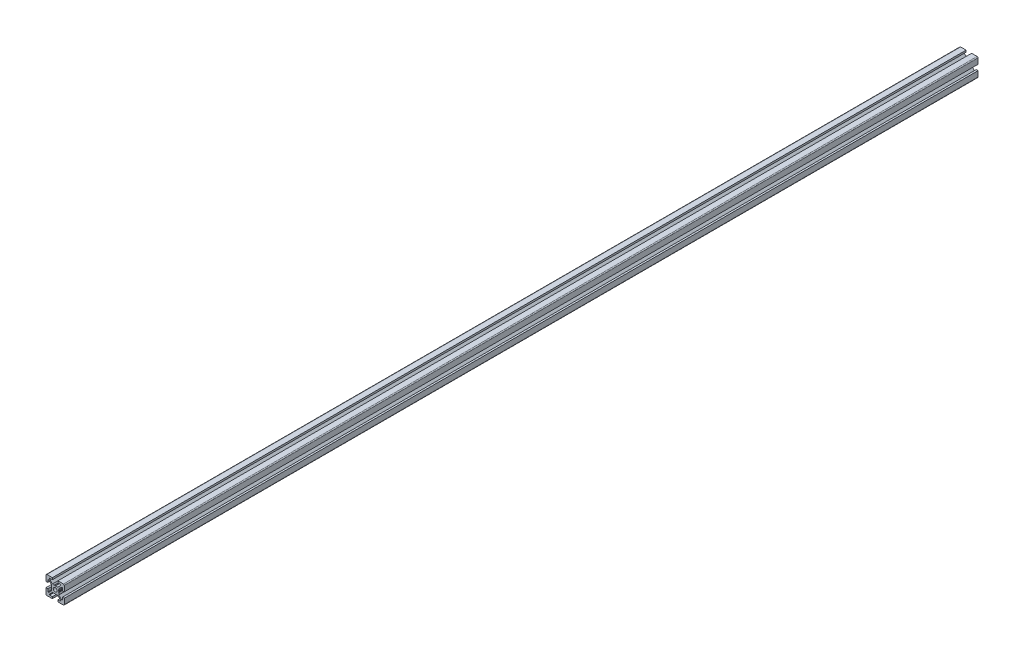
SolidWorks part; units mm, degrees
ref_plane "Front Plane" through (0, 0, 0) normal (0, 0, 1) x (1, 0, 0)
ref_plane "Top Plane" through (0, 0, 0) normal (0, 1, 0) x (1, 0, 0)
ref_plane "Right Plane" through (0, 0, 0) normal (1, 0, 0) x (0, 0, -1)
ref_plane "Plane1" through (0, 0, -2000) normal (0, 0, -1) x (-1, 0, 0)
sketch "Sketch1" plane through (0, 0, -2000) normal (0, 0, -1) x (-1, 0, 0)
  line L0 (10, -3) -> (8, -3)
  line L1 (8, -3) -> (8, -6)
  line L2 (8, -6) -> (7.0607, -6)
  line L3 (7.0607, -6) -> (4, -2.9393)
  line L4 (4, -2.9393) -> (4, -2.5)
  line L5 (4, -2.5) -> (3.751, -1.2189)
  line L6 (3.751, -1.2189) -> (3.933, -0.9036)
  line L7 (3.933, -0.4036) -> (3.7, 0)
  line L8 (3.7, 0) -> (3.933, 0.4036)
  line L9 (4, 0.6536) -> (4, 2.9393)
  line L10 (4, 2.9393) -> (7.0607, 6)
  line L11 (7.0607, 6) -> (8, 6)
  line L12 (8, 6) -> (8, 3)
  line L13 (8, 3) -> (10, 3)
  line L14 (10, 3) -> (10, 9)
  line L15 (9, 10) -> (3, 10)
  line L16 (3, 10) -> (3, 8)
  line L17 (3, 8) -> (6, 8)
  line L18 (6, 8) -> (6, 7.0607)
  line L19 (6, 7.0607) -> (2.9393, 4)
  line L20 (2.9393, 4) -> (2.5, 4)
  line L21 (2.5, 4) -> (1.2189, 3.751)
  line L22 (1.2189, 3.751) -> (0.9036, 3.933)
  line L23 (0.4036, 3.933) -> (0, 3.7)
  line L24 (0, 3.7) -> (-0.4036, 3.933)
  line L25 (-0.6536, 4) -> (-2.9393, 4)
  line L26 (-2.9393, 4) -> (-6, 7.0607)
  line L27 (-6, 7.0607) -> (-6, 8)
  line L28 (-6, 8) -> (-3, 8)
  line L29 (-3, 8) -> (-3, 10)
  line L30 (-3, 10) -> (-9, 10)
  line L31 (-10, 9) -> (-10, 3)
  line L32 (-10, 3) -> (-8, 3)
  line L33 (-8, 3) -> (-8, 6)
  line L34 (-8, 6) -> (-7.0607, 6)
  line L35 (-7.0607, 6) -> (-4, 2.9393)
  line L36 (-4, 2.9393) -> (-4, 2.5)
  line L37 (-4, 2.5) -> (-3.751, 1.2189)
  line L38 (-3.751, 1.2189) -> (-3.933, 0.9036)
  line L39 (-3.933, 0.4036) -> (-3.7, 0)
  line L40 (-3.7, 0) -> (-3.933, -0.4036)
  line L41 (-4, -0.6536) -> (-4, -2.9393)
  line L42 (-4, -2.9393) -> (-7.0607, -6)
  line L43 (-7.0607, -6) -> (-8, -6)
  line L44 (-8, -6) -> (-8, -3)
  line L45 (-8, -3) -> (-10, -3)
  line L46 (-10, -3) -> (-10, -9)
  line L47 (-9, -10) -> (-3, -10)
  line L48 (-3, -10) -> (-3, -8)
  line L49 (-3, -8) -> (-6, -8)
  line L50 (-6, -8) -> (-6, -7.0607)
  line L51 (-6, -7.0607) -> (-2.9393, -4)
  line L52 (-2.9393, -4) -> (-2.5, -4)
  line L53 (-2.5, -4) -> (-1.2189, -3.751)
  line L54 (-1.2189, -3.751) -> (-0.9036, -3.933)
  line L55 (-0.4036, -3.933) -> (0, -3.7)
  line L56 (0, -3.7) -> (0.4036, -3.933)
  line L57 (0.6536, -4) -> (2.9393, -4)
  line L58 (2.9393, -4) -> (6, -7.0607)
  line L59 (6, -7.0607) -> (6, -8)
  line L60 (6, -8) -> (3, -8)
  line L61 (3, -8) -> (3, -10)
  line L62 (3, -10) -> (9, -10)
  line L63 (10, -9) -> (10, -3)
  circle A0 centre (0, 0) radius 2.1
  arc A1 (3.933, -0.9036) -> (3.933, -0.4036) centre (3.5, -0.6536) ccw
  arc A2 (3.933, 0.4036) -> (4, 0.6536) centre (3.5, 0.6536) ccw
  arc A3 (10, 9) -> (9, 10) centre (9, 9) ccw
  arc A4 (0.9036, 3.933) -> (0.4036, 3.933) centre (0.6536, 3.5) ccw
  arc A5 (-0.4036, 3.933) -> (-0.6536, 4) centre (-0.6536, 3.5) ccw
  arc A6 (-9, 10) -> (-10, 9) centre (-9, 9) ccw
  arc A7 (-3.933, 0.9036) -> (-3.933, 0.4036) centre (-3.5, 0.6536) ccw
  arc A8 (-3.933, -0.4036) -> (-4, -0.6536) centre (-3.5, -0.6536) ccw
  arc A9 (-10, -9) -> (-9, -10) centre (-9, -9) ccw
  arc A10 (-0.9036, -3.933) -> (-0.4036, -3.933) centre (-0.6536, -3.5) ccw
  arc A11 (0.4036, -3.933) -> (0.6536, -4) centre (0.6536, -3.5) ccw
  arc A12 (9, -10) -> (10, -9) centre (9, -9) ccw
extrude "Boss-Extrude1" add sketch "Sketch1" against normal blind 1000
